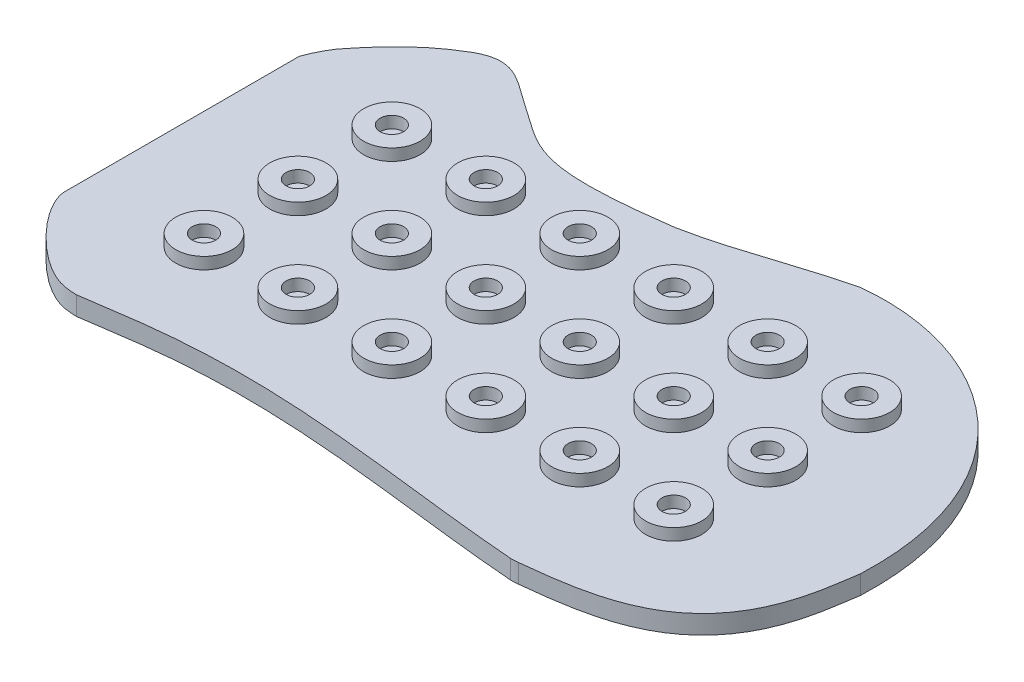
SolidWorks part; units mm, degrees
ref_plane "Front Plane" through (0, 0, 0) normal (0, 0, 1) x (1, 0, 0)
ref_plane "Top Plane" through (0, 0, 0) normal (0, 1, 0) x (1, 0, 0)
ref_plane "Right Plane" through (0, 0, 0) normal (1, 0, 0) x (0, 0, -1)
sketch "Sketch1" plane through (0, 0, 0) normal (0, 1, 0) x (1, 0, 0)
  line L0 (-78.6109, 24.9032) -> (-78.6109, -25.142)
  line L1 (78.526, -10.9955) -> (-78.6109, -10.9955) construction
  line L2 (-77.6109, 24.7348) -> (-77.6109, -25.142)
  line L3 (78.526, -11.9955) -> (-78.6109, -11.9955)
  arc A0 (37.4157, -46.3273) -> (39.1437, -46.2432) centre (37.8097, -36.6353) ccw
  arc A1 (37.4725, -45.3288) -> (39.0215, -45.2505) centre (37.8097, -36.6353) ccw
  spline S0 degree 3 poles (-77.6109, -25.142) (-77.6103, -25.4) (-77.563, -25.903) (-77.2897, -26.9857) (-76.6417, -28.5306) (-75.4978, -30.4481) (-73.6058, -33.039) (-70.8033, -36.112) (-67.3274, -39.127) (-64.1402, -41.244) (-61.4556, -42.4361) (-59.2812, -42.8778) (-58.0256, -42.9092) (-57.3728, -42.9466) knots 0.000484 0.000484 0.000484 0.000484 0.031521 0.062558 0.124632 0.186706 0.248781 0.372929 0.497077 0.621225 0.745373 0.869521 0.993669 0.993669 0.993669 0.993669
  spline S1 degree 3 poles (-57.3728, -42.9466) (-57.1306, -42.9172) (-56.6559, -42.8572) (-55.6329, -42.7168) (-54.2832, -42.5176) (-52.5297, -42.2482) (-50.0282, -41.8652) (-46.6003, -41.367) (-42.0363, -40.8111) (-37.0514, -40.3559) (-29.8812, -39.9429) (-20.0109, -39.8766) (-6.9377, -40.6174) (4.791, -41.8163) (14.5692, -42.9593) (22.0672, -43.8389) (29.7001, -44.6718) (34.8871, -45.1373) (37.4725, -45.3288) knots 0.000538 0.000538 0.000538 0.000538 0.016152 0.031766 0.062993 0.094221 0.125449 0.187904 0.250359 0.312815 0.37527 0.50018 0.625091 0.750001 0.812457 0.874912 0.937367 0.999822 0.999822 0.999822 0.999822
  spline S2 degree 3 poles (39.0215, -45.2505) (40.5541, -45.0873) (43.6362, -44.7445) (49.6297, -43.8727) (56.6431, -42.2158) (63.7646, -38.9137) (69.3225, -34.2155) (72.596, -29.3087) (74.4639, -25.0567) (75.5267, -21.803) (76.2971, -18.6022) (76.7457, -16.0939) (77.026, -14.2578) (77.207, -12.9947) (77.3723, -11.8407) (77.4763, -11.2132) (77.5311, -10.8821) knots -0.000309 -0.000309 -0.000309 -0.000309 0.063093 0.126495 0.253299 0.380104 0.506908 0.633712 0.697114 0.760516 0.823918 0.88732 0.919021 0.950722 0.982423 1.014124 1.014124 1.014124 1.014124
  spline S3 degree 3 poles (77.5311, -10.8821) (77.5748, -9.7665) (77.6099, -7.5074) (77.4888, -4.2729) (77.2058, -1.1252) (76.6195, 2.9373) (75.5088, 7.7538) (72.9895, 14.9059) (68.5668, 22.78) (61.5957, 30.4634) (53.3357, 36.3146) (44.1583, 40.2648) (34.4498, 42.2506) (27.8575, 42.2059) (24.6064, 41.8434) knots 0.000169 0.000169 0.000169 0.000169 0.031414 0.062658 0.093902 0.125147 0.187635 0.250124 0.375101 0.500079 0.625056 0.750034 0.875011 0.999988 0.999988 0.999988 0.999988
  spline S4 degree 3 poles (24.6064, 41.8434) (19.4417, 40.5996) (11.8686, 38.1019) (1.7069, 34.9414) (-3.4909, 33.6615) (-6.1131, 33.1605) knots 0.000659 0.000659 0.000659 0.000659 0.498067 0.746772 0.995476 0.995476 0.995476 0.995476
  spline S5 degree 3 poles (-6.1131, 33.1605) (-7.1417, 33.0163) (-9.1825, 32.742) (-13.4171, 32.237) (-18.6364, 31.7654) (-24.3553, 31.6023) (-29.2844, 31.96) (-33.4204, 32.9216) (-36.3715, 34.2616) (-38.6497, 35.6481) (-40.393, 36.836) (-41.9608, 37.95) (-43.3176, 38.8994) (-44.0701, 39.4107) (-44.4391, 39.6587) knots -0.000196 -0.000196 -0.000196 -0.000196 0.062587 0.12537 0.250936 0.376501 0.502067 0.627632 0.753198 0.815981 0.878764 0.941546 0.972938 1.004329 1.004329 1.004329 1.004329
  spline S6 degree 3 poles (-44.4391, 39.6587) (-44.6983, 39.8375) (-45.2219, 40.2027) (-46.2044, 40.9033) (-47.345, 41.7292) (-48.5998, 42.6198) (-50.1509, 43.6513) (-51.9146, 44.6189) (-53.8615, 45.2294) (-55.7055, 45.3275) (-57.1648, 45.051) (-58.2486, 44.6839) (-59.0003, 44.3616) (-59.6837, 44.0129) (-60.0375, 43.8061) (-60.2239, 43.694) knots -0.002497 -0.002497 -0.002497 -0.002497 0.029066 0.060629 0.123754 0.18688 0.250006 0.376257 0.502509 0.62876 0.755012 0.818137 0.881263 0.944389 1.007515 1.007515 1.007515 1.007515
  spline S7 degree 3 poles (-78.6109, -25.142) (-78.6097, -25.7822) (-78.3711, -27.0076) (-77.5216, -29.0127) (-76.3076, -31.0396) (-74.3365, -33.7283) (-71.4439, -36.8883) (-67.8634, -39.9802) (-64.5529, -42.1647) (-61.6917, -43.4202) (-59.6968, -43.8088) (-58.2959, -43.9054) (-57.6656, -43.9305) (-57.3419, -43.9502) knots 0.000409 0.000409 0.000409 0.000409 0.062843 0.125276 0.18771 0.250143 0.375011 0.499878 0.624745 0.749612 0.874479 0.936913 0.999346 0.999346 0.999346 0.999346
  spline S8 degree 3 poles (-57.3419, -43.9502) (-57.0965, -43.9206) (-56.6141, -43.8604) (-55.5847, -43.7202) (-54.2292, -43.5208) (-52.4771, -43.2519) (-49.983, -42.8696) (-46.5727, -42.3725) (-42.0367, -41.817) (-37.0824, -41.3612) (-29.9535, -40.9457) (-20.1287, -40.874) (-7.0907, -41.608) (4.6318, -42.8047) (14.4219, -43.9489) (21.9389, -44.8307) (29.5994, -45.6669) (34.8166, -46.135) (37.4157, -46.3273) knots -0.001373 -0.001373 -0.001373 -0.001373 0.014273 0.029919 0.06121 0.092502 0.123794 0.186377 0.24896 0.311543 0.374127 0.499293 0.62446 0.749626 0.81221 0.874793 0.937376 0.99996 0.99996 0.99996 0.99996
  spline S9 degree 3 poles (39.1437, -46.2432) (40.686, -46.0789) (43.7818, -45.7344) (49.848, -44.8507) (56.9964, -43.16) (64.3453, -39.7462) (70.1244, -34.8409) (73.5118, -29.7304) (75.4294, -25.3355) (76.5134, -21.9918) (77.2941, -18.7213) (77.7459, -16.1748) (78.0266, -14.3264) (78.2075, -13.0606) (78.3702, -11.9307) (78.4738, -11.3105) (78.5279, -10.984) knots -0.000086 -0.000086 -0.000086 -0.000086 0.063428 0.126941 0.253967 0.380993 0.50802 0.635046 0.698559 0.762072 0.825585 0.889098 0.920855 0.952612 0.984368 1.016125 1.016125 1.016125 1.016125
  spline S10 degree 3 poles (78.5279, -10.984) (78.5733, -9.8502) (78.6109, -7.5559) (78.4906, -4.2601) (78.2049, -1.0549) (77.6104, 3.0871) (76.4803, 8.0028) (73.9108, 15.31) (69.3901, 23.3646) (62.2582, 31.2245) (53.8088, 37.2052) (44.4261, 41.2372) (34.4991, 43.2588) (27.7571, 43.2053) (24.4331, 42.8302) knots -0.000407 -0.000407 -0.000407 -0.000407 0.03088 0.062166 0.093453 0.12474 0.187314 0.249888 0.375035 0.500183 0.62533 0.750478 0.875625 1.000773 1.000773 1.000773 1.000773
  spline S11 degree 3 poles (24.4331, 42.8302) (21.8301, 42.2051) (16.6685, 40.7402) (6.525, 37.4536) (-1.0744, 35.1413) (-6.2764, 34.1474) knots -0.001281 -0.001281 -0.001281 -0.001281 0.247714 0.49671 0.9947 0.9947 0.9947 0.9947
  spline S12 degree 3 poles (-6.2764, 34.1474) (-7.3001, 34.0039) (-9.3317, 33.7312) (-13.542, 33.2295) (-18.7181, 32.7628) (-24.3556, 32.604) (-29.1564, 32.9561) (-33.1061, 33.8787) (-35.9015, 35.1472) (-38.1022, 36.4854) (-39.8157, 37.6526) (-41.3786, 38.7631) (-42.7458, 39.7198) (-43.5043, 40.2353) (-43.8763, 40.4853) knots 0.000305 0.000305 0.000305 0.000305 0.063048 0.125791 0.251276 0.376761 0.502247 0.627732 0.753218 0.815961 0.878703 0.941446 0.972817 1.004189 1.004189 1.004189 1.004189
  spline S13 degree 3 poles (-43.8763, 40.4853) (-44.1324, 40.662) (-44.6496, 41.0228) (-45.6222, 41.7163) (-46.7618, 42.5415) (-48.0307, 43.4423) (-49.6264, 44.5037) (-51.4979, 45.535) (-53.6685, 46.2221) (-55.7733, 46.3353) (-57.4106, 46.0235) (-58.6015, 45.6208) (-59.4227, 45.2686) (-60.0246, 44.9622) (-60.4597, 44.7184) (-60.6399, 44.6107) (-60.7341, 44.5541) knots -0.002294 -0.002294 -0.002294 -0.002294 0.029245 0.060783 0.12386 0.186936 0.250013 0.376167 0.50232 0.628473 0.754627 0.817704 0.88078 0.943857 0.975396 1.006934 1.006934 1.006934 1.006934
  spline S14 degree 3 poles (-60.7341, 44.5541) (-61.1687, 44.2998) (-62.0358, 43.7712) (-63.676, 42.6889) (-66.3643, 40.7074) (-69.6969, 37.7112) (-72.4782, 34.663) (-74.193, 32.5981) (-75.1195, 31.4458) (-75.5587, 30.8903) (-75.7803, 30.6092) knots 0.000427 0.000427 0.000427 0.000427 0.063268 0.126109 0.251792 0.503158 0.754524 0.880206 0.943048 1.005889 1.005889 1.005889 1.005889
  spline S15 degree 3 poles (-60.2239, 43.694) (-60.6474, 43.4463) (-61.4924, 42.9314) (-63.0906, 41.8773) (-65.7124, 39.9465) (-68.9709, 37.0199) (-71.6981, 34.0358) (-73.6437, 31.6948) (-74.5236, 30.5881) (-74.9696, 30.0223) knots 0.000174 0.000174 0.000174 0.000174 0.062881 0.125589 0.251004 0.501833 0.752662 0.878077 1.003492 1.003492 1.003492 1.003492
  spline S16 degree 3 poles (-74.9696, 30.0223) (-75.5195, 29.1919) (-76.5302, 27.448) (-77.2874, 25.6577) (-77.6109, 24.7348) knots 0.499549 0.499549 0.499549 0.499549 0.499766 0.499983 0.499983 0.499983 0.499983
  spline S17 degree 3 poles (-75.7803, 30.6092) (-76.3738, 29.7162) (-77.4602, 27.8403) (-78.2688, 25.9015) (-78.6109, 24.9032) knots 0.499546 0.499546 0.499546 0.499546 0.49977 0.499995 0.499995 0.499995 0.499995
  point P0 (0.0094, -10.9955)
extrude "Boss-Extrude2" add sketch "Sketch1" along normal blind 4 contours L1 S2 S3 S4 S5 S6 S15 S16 L2 | S2 L1 L2 L3 | A1 S2 L3 L2 S0 S1
ref_plane "Plane1" through (0, 0, -24.7348) normal (0, 0, -1) x (0, -1, 0)
sketch "Sketch2" plane through (0, 4, 0) normal (0, 1, 0) x (1, 0, 0)
  circle A0 centre (-52.6013, 19.445) radius 6
extrude "Boss-Extrude3" add sketch "Sketch2" along normal blind 2.5
sketch "Sketch4" plane through (0, 6.5, 0) normal (0, 1, 0) x (1, 0, 0)
  circle A0 centre (-52.6013, 19.445) radius 2.5
extrude "Cut-Extrude1" cut sketch "Sketch4" against normal blind 2.5
pattern_linear "LPattern1" count 3 spacing 20 along (0, 0, 1) count 6 spacing 20 along (1, 0, 0) of "Cut-Extrude1", "Boss-Extrude3"
